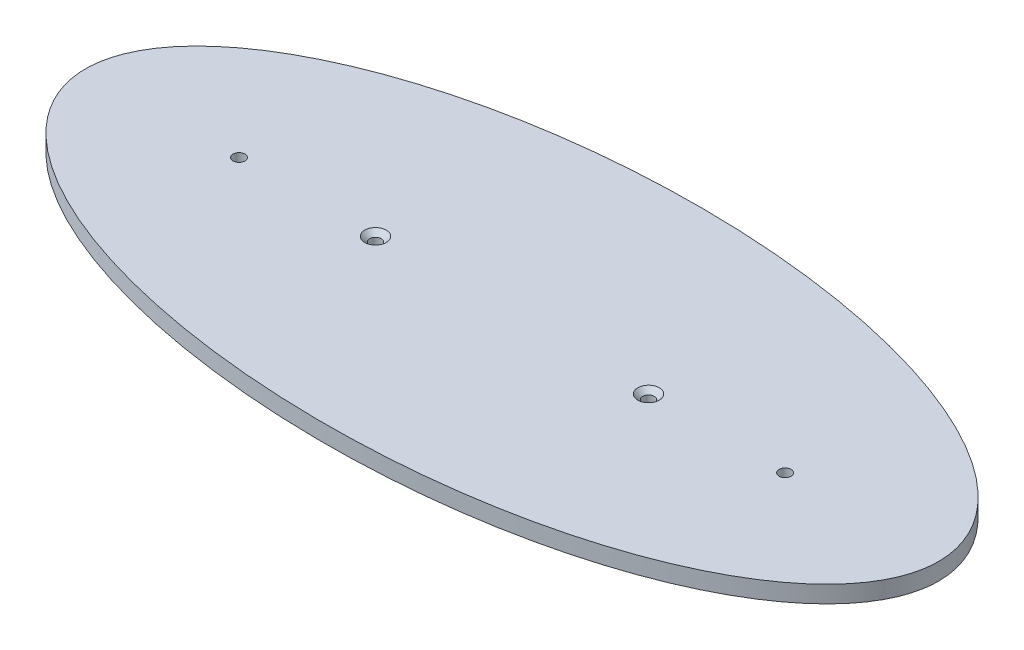
SolidWorks part; units mm, degrees
ref_plane "正面" through (0, 0, 0) normal (0, 0, 1) x (1, 0, 0)
ref_plane "平面" through (0, 0, 0) normal (0, 1, 0) x (1, 0, 0)
ref_plane "右側面" through (0, 0, 0) normal (1, 0, 0) x (0, 0, -1)
sketch "ｽｹｯﾁ1" plane through (0, 0, 0) normal (0, 1, 0) x (1, 0, 0)
  ellipse E0 centre (0, 0) end of major axis (125, 0) minor radius 55
extrude "ﾎﾞｽ - 押し出し1" add sketch "ｽｹｯﾁ1" along normal blind 5
hole_wizard "M3 丸皿小ねじ用皿穴1" positions "ｽｹｯﾁ7" profile "ｽｹｯﾁ6" countersink size "M3" standard "ANSIﾒｰﾄﾙ" end condition through all
sketch "ｽｹｯﾁ7" plane through (0, 5, 0) normal (0, 1, 0) x (-1, 0, 0)
  point P0 (40, 0)
  point P1 (-40, 0)
  dimension "D1" = 40
  dimension "D2" = 80
sketch "ｽｹｯﾁ6" plane through (-40, 5, 0) normal (1, 0, 0) x (0, 0, 1)
  line L0 (0, 0) -> (0, 5)
  line L1 (0, 5) -> (1.7, 5)
  line L2 (1.7, 5) -> (1.7, 1.45)
  line L3 (1.7, 1.45) -> (3.15, 0)
  line L5 (3.15, 0) -> (0, 0)
  line L6 (-1.7, 1.45) -> (-3.15, 0) construction
  line L11 (0, -6.35) -> (0, 107.95) construction
  dimension "通し穴の直径" = 3.4
  dimension "通し穴の深さ" = 5
  dimension "表面の皿穴の直径" = 6.3
  dimension "表面の皿穴の角度" = 90
sketch "ｽｹｯﾁ8" plane through (0, 5, 0) normal (0, 1, 0) x (1, 0, 0)
  circle A0 centre (-80, 0) radius 1.75
  circle A1 centre (80, 0) radius 1.75
  dimension "D3" = 3.5
  dimension "D4" = 3.5
  dimension "D1" = 80
  dimension "D2" = 160
extrude "ｶｯﾄ - 押し出し1" cut sketch "ｽｹｯﾁ8" against normal through all
